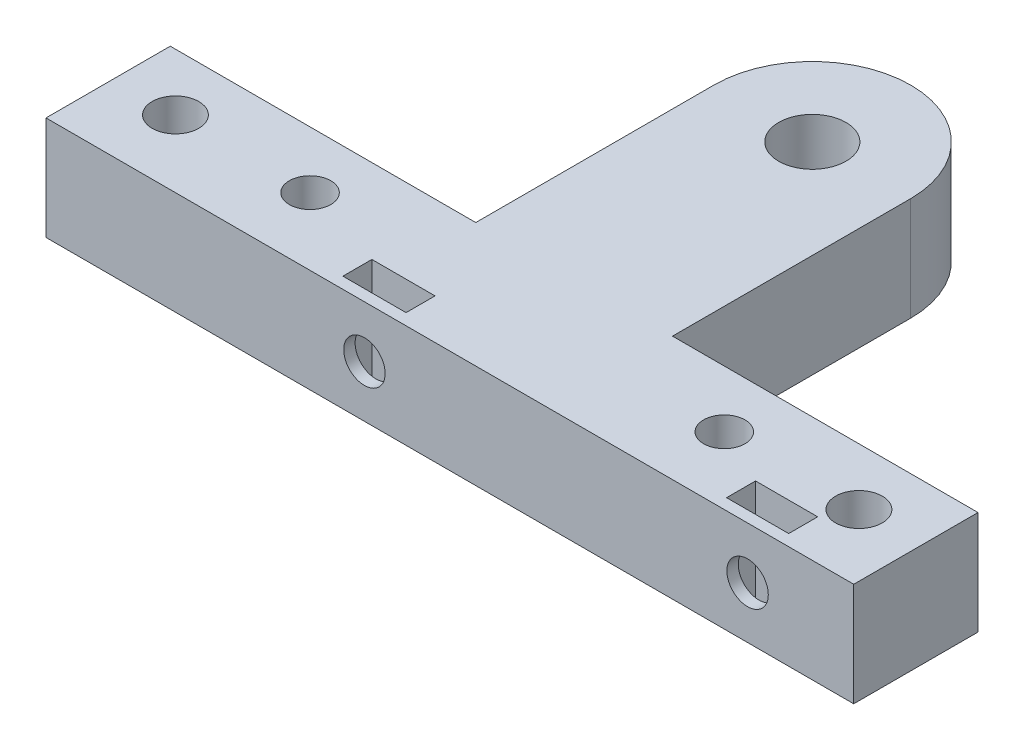
SolidWorks part; units mm, degrees
ref_plane "Ön Düzlem" through (0, 0, 0) normal (0, 0, 1) x (1, 0, 0)
ref_plane "Üst Düzlem" through (0, 0, 0) normal (0, 1, 0) x (1, 0, 0)
ref_plane "Sağ Düzlem" through (0, 0, 0) normal (1, 0, 0) x (0, 0, -1)
sketch "Çizim1" plane through (0, 0, 0) normal (0, 1, 0) x (1, 0, 0)
  line L0 (9.5, 6) -> (39, 6)
  line L1 (-39, 6) -> (-9.5, 6)
  line L2 (-39, 6) -> (-39, -6)
  line L3 (-39, -6) -> (39, -6)
  line L4 (39, 6) -> (39, -6)
  line L7 (-9.5, 6) -> (-9.5, 29)
  line L8 (9.5, 29) -> (9.5, 6)
  circle A0 centre (0, 29) radius 3.25
  arc A1 (9.5, 29) -> (-9.5, 29) centre (0, 29) ccw
  circle A2 centre (-33, 0.5) radius 2.25
  circle A3 centre (33, 0.5) radius 2.25
  point P0 (0, 0)
extrude "Yükseklik-Ekstrüzyon1" add sketch "Çizim1" along normal blind 10
sketch "Çizim2" plane through (0, 0, 0) normal (0, -1, 0) x (1, 0, 0)
  line L1 (5.75, -29) -> (2.875, -24.0204)
  line L2 (2.875, -24.0204) -> (-2.875, -24.0204)
  line L3 (-2.875, -24.0204) -> (-5.75, -29)
  line L4 (-5.75, -29) -> (-2.875, -33.9796)
  line L5 (-2.875, -33.9796) -> (2.875, -33.9796)
  line L6 (2.875, -33.9796) -> (5.75, -29)
  circle A0 centre (0, -29) radius 4.9796 construction
  dimension "D1" = 11.5
extrude "Kes-Ekstrüzyon1" cut sketch "Çizim2" against normal blind 5
sketch "Çizim3" plane through (0, 0, 6) normal (0, 0, 1) x (1, 0, 0)
  circle A1 centre (-8.25, 5) radius 2
  circle A2 centre (28.75, 5) radius 2
extrude "Kes-Ekstrüzyon4" cut sketch "Çizim3" against normal blind 4
sketch "Çizim4" plane through (0, 10, 0) normal (0, 1, 0) x (1, 0, 0)
  line L4 (-11.4309, -2.1) -> (-5.3309, -2.1)
  line L5 (-11.4309, -2.1) -> (-11.4309, -4.9)
  line L6 (-11.4309, -4.9) -> (-5.3309, -4.9)
  line L7 (-5.3309, -2.1) -> (-5.3309, -4.9)
  line L8 (-11.4309, -2.1) -> (-5.3309, -4.9) construction
  line L9 (-11.4309, -4.9) -> (-5.3309, -2.1) construction
  line L10 (25.6191, -2.1) -> (31.6191, -2.1)
  line L11 (25.6191, -2.1) -> (25.6191, -4.9)
  line L12 (25.6191, -4.9) -> (31.6191, -4.9)
  line L13 (31.6191, -2.1) -> (31.6191, -4.9)
  line L14 (25.6191, -2.1) -> (31.6191, -4.9) construction
  line L15 (25.6191, -4.9) -> (31.6191, -2.1) construction
  dimension "D1" = 6
extrude "Kes-Ekstrüzyon5" cut sketch "Çizim4" against normal blind 10
sketch "Çizim5" plane through (0, 0, 2) normal (0, 0, 1) x (1, 0, 0)
  circle A0 centre (-8.25, 5) radius 1.65
  circle A2 centre (28.75, 5) radius 1.65
extrude "Kes-Ekstrüzyon6" cut sketch "Çizim5" against normal blind 5
sketch "Çizim6" plane through (0, 10, 0) normal (0, 1, 0) x (1, 0, 0)
  circle A0 centre (-20, 0.5) radius 2
  circle A1 centre (20, 0.5) radius 2
extrude "Kes-Ekstrüzyon7" cut sketch "Çizim6" against normal blind 13
